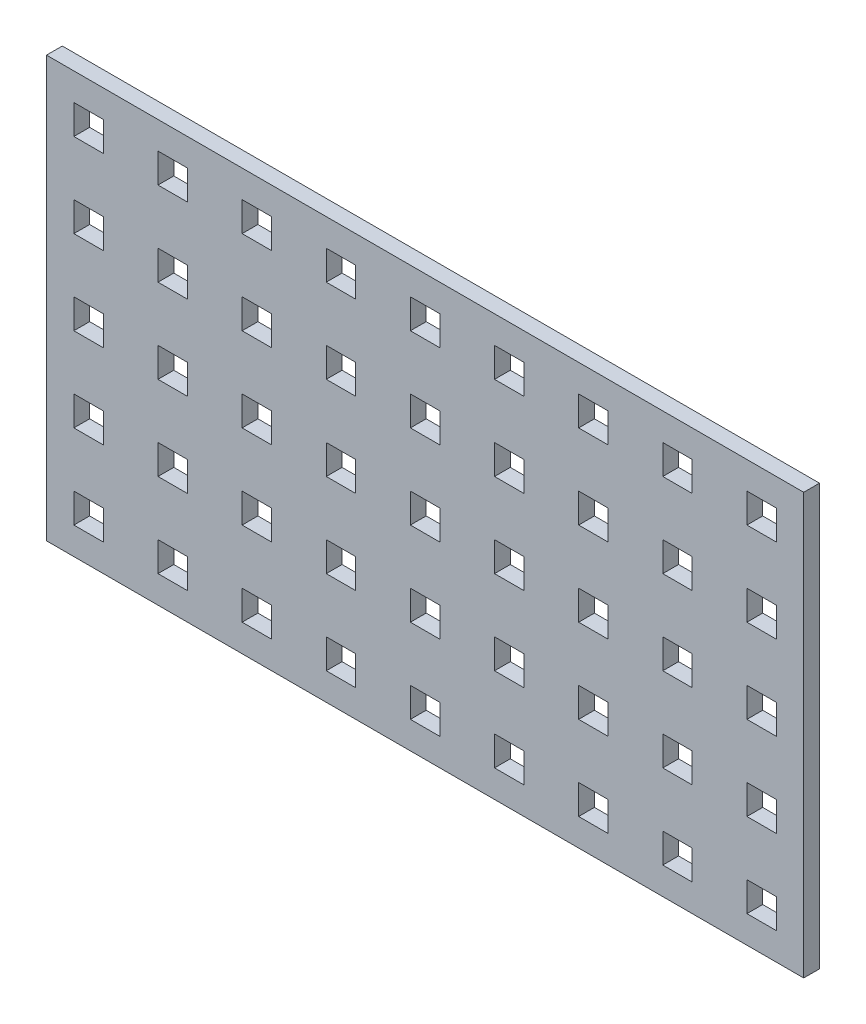
SolidWorks part; units mm, degrees
ref_plane "Plano frontal" through (0, 0, 0) normal (0, 0, 1) x (1, 0, 0)
ref_plane "Plano superior" through (0, 0, 0) normal (0, 1, 0) x (1, 0, 0)
ref_plane "Plano direito" through (0, 0, 0) normal (1, 0, 0) x (0, 0, -1)
sketch "Esboço1" plane through (0, 0, 0) normal (0, 0, 1) x (1, 0, 0)
  line L0 (-36, 0) -> (-32, 0) construction
  line L1 (-36, 20) -> (36, 20)
  line L2 (-36, 20) -> (-36, -20)
  line L3 (-36, -20) -> (36, -20)
  line L4 (36, 20) -> (36, -20)
  line L5 (-36, 20) -> (36, -20) construction
  line L6 (-36, -20) -> (36, 20) construction
  line L7 (-32, 0) -> (-32, 16) construction
  line L8 (-32, 16) -> (32, 16) construction
  line L9 (-33.4, 17.4) -> (-33.4, 14.6)
  line L10 (-25.4, 17.4) -> (-25.4, 14.6)
  line L11 (-22.6, 17.4) -> (-22.6, 14.6)
  line L12 (-25.4, 14.6) -> (-22.6, 14.6)
  line L13 (-25.4, 17.4) -> (-22.6, 17.4)
  line L14 (-25.4, 9.4) -> (-25.4, 6.6)
  line L15 (-22.6, 9.4) -> (-22.6, 6.6)
  line L16 (-30.6, 17.4) -> (-30.6, 14.6)
  line L17 (-33.4, 14.6) -> (-30.6, 14.6)
  line L18 (-33.4, 17.4) -> (-30.6, 14.6) construction
  line L19 (-33.4, 17.4) -> (-30.6, 17.4)
  line L20 (-33.4, 14.6) -> (-30.6, 17.4) construction
  line L21 (30.6, 17.4) -> (30.6, 14.6)
  line L22 (33.4, 17.4) -> (33.4, 14.6)
  line L23 (30.6, 14.6) -> (33.4, 14.6)
  line L24 (30.6, 17.4) -> (33.4, 14.6) construction
  line L25 (30.6, 17.4) -> (33.4, 17.4)
  line L26 (30.6, 14.6) -> (33.4, 17.4) construction
  line L27 (-33.4, 9.4) -> (-33.4, 6.6)
  line L28 (-30.6, 9.4) -> (-30.6, 6.6)
  line L29 (-33.4, 6.6) -> (-30.6, 6.6)
  line L30 (-33.4, 9.4) -> (-30.6, 9.4)
  line L31 (-33.4, 9.4) -> (-30.6, 6.6) construction
  line L32 (-33.4, 6.6) -> (-30.6, 9.4) construction
  line L33 (30.6, 9.4) -> (30.6, 6.6)
  line L34 (33.4, 9.4) -> (33.4, 6.6)
  line L35 (30.6, 6.6) -> (33.4, 6.6)
  line L36 (30.6, 9.4) -> (33.4, 9.4)
  line L37 (30.6, 9.4) -> (33.4, 6.6) construction
  line L38 (30.6, 6.6) -> (33.4, 9.4) construction
  line L39 (-33.4, 1.4) -> (-33.4, -1.4)
  line L40 (-30.6, 1.4) -> (-30.6, -1.4)
  line L41 (-33.4, -1.4) -> (-30.6, -1.4)
  line L42 (-33.4, 1.4) -> (-30.6, 1.4)
  line L43 (-33.4, 1.4) -> (-30.6, -1.4) construction
  line L44 (-33.4, -1.4) -> (-30.6, 1.4) construction
  line L45 (30.6, 1.4) -> (30.6, -1.4)
  line L46 (33.4, 1.4) -> (33.4, -1.4)
  line L47 (30.6, -1.4) -> (33.4, -1.4)
  line L48 (30.6, 1.4) -> (33.4, 1.4)
  line L49 (30.6, 1.4) -> (33.4, -1.4) construction
  line L50 (30.6, -1.4) -> (33.4, 1.4) construction
  line L51 (-33.4, -6.6) -> (-33.4, -9.4)
  line L52 (-30.6, -6.6) -> (-30.6, -9.4)
  line L53 (-33.4, -9.4) -> (-30.6, -9.4)
  line L54 (-33.4, -6.6) -> (-30.6, -6.6)
  line L55 (-33.4, -6.6) -> (-30.6, -9.4) construction
  line L56 (-33.4, -9.4) -> (-30.6, -6.6) construction
  line L57 (30.6, -6.6) -> (30.6, -9.4)
  line L58 (33.4, -6.6) -> (33.4, -9.4)
  line L59 (30.6, -9.4) -> (33.4, -9.4)
  line L60 (30.6, -6.6) -> (33.4, -6.6)
  line L61 (30.6, -6.6) -> (33.4, -9.4) construction
  line L62 (30.6, -9.4) -> (33.4, -6.6) construction
  line L63 (-33.4, -14.6) -> (-33.4, -17.4)
  line L64 (-30.6, -14.6) -> (-30.6, -17.4)
  line L65 (-33.4, -17.4) -> (-30.6, -17.4)
  line L66 (-33.4, -14.6) -> (-30.6, -14.6)
  line L67 (-33.4, -14.6) -> (-30.6, -17.4) construction
  line L68 (-33.4, -17.4) -> (-30.6, -14.6) construction
  line L69 (30.6, -14.6) -> (30.6, -17.4)
  line L70 (33.4, -14.6) -> (33.4, -17.4)
  line L71 (30.6, -17.4) -> (33.4, -17.4)
  line L72 (30.6, -14.6) -> (33.4, -14.6)
  line L73 (30.6, -14.6) -> (33.4, -17.4) construction
  line L74 (30.6, -17.4) -> (33.4, -14.6) construction
  line L75 (-25.4, 6.6) -> (-22.6, 6.6)
  line L76 (-25.4, 9.4) -> (-22.6, 9.4)
  line L77 (-25.4, 1.4) -> (-25.4, -1.4)
  line L78 (-22.6, 1.4) -> (-22.6, -1.4)
  line L79 (-25.4, -1.4) -> (-22.6, -1.4)
  line L80 (-25.4, 1.4) -> (-22.6, 1.4)
  line L81 (-25.4, -6.6) -> (-25.4, -9.4)
  line L82 (-22.6, -6.6) -> (-22.6, -9.4)
  line L83 (-25.4, -9.4) -> (-22.6, -9.4)
  line L84 (-25.4, -6.6) -> (-22.6, -6.6)
  line L85 (-25.4, -14.6) -> (-25.4, -17.4)
  line L86 (-22.6, -14.6) -> (-22.6, -17.4)
  line L87 (-25.4, -17.4) -> (-22.6, -17.4)
  line L88 (-25.4, -14.6) -> (-22.6, -14.6)
  line L89 (-24, 0) -> (-24, 16) construction
  line L90 (-25.4, 17.4) -> (-22.6, 14.6) construction
  line L91 (-25.4, 14.6) -> (-22.6, 17.4) construction
  line L92 (-25.4, 9.4) -> (-22.6, 6.6) construction
  line L93 (-25.4, 6.6) -> (-22.6, 9.4) construction
  line L94 (-25.4, 1.4) -> (-22.6, -1.4) construction
  line L95 (-25.4, -1.4) -> (-22.6, 1.4) construction
  line L96 (-25.4, -6.6) -> (-22.6, -9.4) construction
  line L97 (-25.4, -9.4) -> (-22.6, -6.6) construction
  line L98 (-25.4, -14.6) -> (-22.6, -17.4) construction
  line L99 (-25.4, -17.4) -> (-22.6, -14.6) construction
  line L100 (-17.4, 17.4) -> (-17.4, 14.6)
  line L101 (-14.6, 17.4) -> (-14.6, 14.6)
  line L102 (-17.4, 14.6) -> (-14.6, 14.6)
  line L103 (-17.4, 17.4) -> (-14.6, 17.4)
  line L104 (-17.4, 9.4) -> (-17.4, 6.6)
  line L105 (-14.6, 9.4) -> (-14.6, 6.6)
  line L106 (-17.4, 6.6) -> (-14.6, 6.6)
  line L107 (-17.4, 9.4) -> (-14.6, 9.4)
  line L108 (-17.4, 1.4) -> (-17.4, -1.4)
  line L109 (-14.6, 1.4) -> (-14.6, -1.4)
  line L110 (-17.4, -1.4) -> (-14.6, -1.4)
  line L111 (-17.4, 1.4) -> (-14.6, 1.4)
  line L112 (-17.4, -6.6) -> (-17.4, -9.4)
  line L113 (-14.6, -6.6) -> (-14.6, -9.4)
  line L114 (-17.4, -9.4) -> (-14.6, -9.4)
  line L115 (-17.4, -6.6) -> (-14.6, -6.6)
  line L116 (-17.4, -14.6) -> (-17.4, -17.4)
  line L117 (-14.6, -14.6) -> (-14.6, -17.4)
  line L118 (-17.4, -17.4) -> (-14.6, -17.4)
  line L119 (-17.4, -14.6) -> (-14.6, -14.6)
  line L120 (-16, 0) -> (-16, 16) construction
  line L121 (-17.4, 17.4) -> (-14.6, 14.6) construction
  line L122 (-17.4, 14.6) -> (-14.6, 17.4) construction
  line L123 (-17.4, 9.4) -> (-14.6, 6.6) construction
  line L124 (-17.4, 6.6) -> (-14.6, 9.4) construction
  line L125 (-17.4, 1.4) -> (-14.6, -1.4) construction
  line L126 (-17.4, -1.4) -> (-14.6, 1.4) construction
  line L127 (-17.4, -6.6) -> (-14.6, -9.4) construction
  line L128 (-17.4, -9.4) -> (-14.6, -6.6) construction
  line L129 (-17.4, -14.6) -> (-14.6, -17.4) construction
  line L130 (-17.4, -17.4) -> (-14.6, -14.6) construction
  line L131 (-9.4, 17.4) -> (-9.4, 14.6)
  line L132 (-6.6, 17.4) -> (-6.6, 14.6)
  line L133 (-9.4, 14.6) -> (-6.6, 14.6)
  line L134 (-9.4, 17.4) -> (-6.6, 17.4)
  line L135 (-9.4, 9.4) -> (-9.4, 6.6)
  line L136 (-6.6, 9.4) -> (-6.6, 6.6)
  line L137 (-9.4, 6.6) -> (-6.6, 6.6)
  line L138 (-9.4, 9.4) -> (-6.6, 9.4)
  line L139 (-9.4, 1.4) -> (-9.4, -1.4)
  line L140 (-6.6, 1.4) -> (-6.6, -1.4)
  line L141 (-9.4, -1.4) -> (-6.6, -1.4)
  line L142 (-9.4, 1.4) -> (-6.6, 1.4)
  line L143 (-9.4, -6.6) -> (-9.4, -9.4)
  line L144 (-6.6, -6.6) -> (-6.6, -9.4)
  line L145 (-9.4, -9.4) -> (-6.6, -9.4)
  line L146 (-9.4, -6.6) -> (-6.6, -6.6)
  line L147 (-9.4, -14.6) -> (-9.4, -17.4)
  line L148 (-6.6, -14.6) -> (-6.6, -17.4)
  line L149 (-9.4, -17.4) -> (-6.6, -17.4)
  line L150 (-9.4, -14.6) -> (-6.6, -14.6)
  line L151 (-8, 0) -> (-8, 16) construction
  line L152 (-9.4, 17.4) -> (-6.6, 14.6) construction
  line L153 (-9.4, 14.6) -> (-6.6, 17.4) construction
  line L154 (-9.4, 9.4) -> (-6.6, 6.6) construction
  line L155 (-9.4, 6.6) -> (-6.6, 9.4) construction
  line L156 (-9.4, 1.4) -> (-6.6, -1.4) construction
  line L157 (-9.4, -1.4) -> (-6.6, 1.4) construction
  line L158 (-9.4, -6.6) -> (-6.6, -9.4) construction
  line L159 (-9.4, -9.4) -> (-6.6, -6.6) construction
  line L160 (-9.4, -14.6) -> (-6.6, -17.4) construction
  line L161 (-9.4, -17.4) -> (-6.6, -14.6) construction
  line L162 (-1.4, 17.4) -> (-1.4, 14.6)
  line L163 (1.4, 17.4) -> (1.4, 14.6)
  line L164 (-1.4, 14.6) -> (1.4, 14.6)
  line L165 (-1.4, 17.4) -> (1.4, 17.4)
  line L166 (-1.4, 9.4) -> (-1.4, 6.6)
  line L167 (1.4, 9.4) -> (1.4, 6.6)
  line L168 (-1.4, 6.6) -> (1.4, 6.6)
  line L169 (-1.4, 9.4) -> (1.4, 9.4)
  line L170 (-1.4, 1.4) -> (-1.4, -1.4)
  line L171 (1.4, 1.4) -> (1.4, -1.4)
  line L172 (-1.4, -1.4) -> (1.4, -1.4)
  line L173 (-1.4, 1.4) -> (1.4, 1.4)
  line L174 (-1.4, -6.6) -> (-1.4, -9.4)
  line L175 (1.4, -6.6) -> (1.4, -9.4)
  line L176 (-1.4, -9.4) -> (1.4, -9.4)
  line L177 (-1.4, -6.6) -> (1.4, -6.6)
  line L178 (-1.4, -14.6) -> (-1.4, -17.4)
  line L179 (1.4, -14.6) -> (1.4, -17.4)
  line L180 (-1.4, -17.4) -> (1.4, -17.4)
  line L181 (-1.4, -14.6) -> (1.4, -14.6)
  line L182 (0, 0) -> (0, 16) construction
  line L183 (-1.4, 17.4) -> (1.4, 14.6) construction
  line L184 (-1.4, 14.6) -> (1.4, 17.4) construction
  line L185 (-1.4, 9.4) -> (1.4, 6.6) construction
  line L186 (-1.4, 6.6) -> (1.4, 9.4) construction
  line L187 (-1.4, 1.4) -> (1.4, -1.4) construction
  line L188 (-1.4, -1.4) -> (1.4, 1.4) construction
  line L189 (-1.4, -6.6) -> (1.4, -9.4) construction
  line L190 (-1.4, -9.4) -> (1.4, -6.6) construction
  line L191 (-1.4, -14.6) -> (1.4, -17.4) construction
  line L192 (-1.4, -17.4) -> (1.4, -14.6) construction
  line L193 (6.6, 17.4) -> (6.6, 14.6)
  line L194 (9.4, 17.4) -> (9.4, 14.6)
  line L195 (6.6, 14.6) -> (9.4, 14.6)
  line L196 (6.6, 17.4) -> (9.4, 17.4)
  line L197 (6.6, 9.4) -> (6.6, 6.6)
  line L198 (9.4, 9.4) -> (9.4, 6.6)
  line L199 (6.6, 6.6) -> (9.4, 6.6)
  line L200 (6.6, 9.4) -> (9.4, 9.4)
  line L201 (6.6, 1.4) -> (6.6, -1.4)
  line L202 (9.4, 1.4) -> (9.4, -1.4)
  line L203 (6.6, -1.4) -> (9.4, -1.4)
  line L204 (6.6, 1.4) -> (9.4, 1.4)
  line L205 (6.6, -6.6) -> (6.6, -9.4)
  line L206 (9.4, -6.6) -> (9.4, -9.4)
  line L207 (6.6, -9.4) -> (9.4, -9.4)
  line L208 (6.6, -6.6) -> (9.4, -6.6)
  line L209 (6.6, -14.6) -> (6.6, -17.4)
  line L210 (9.4, -14.6) -> (9.4, -17.4)
  line L211 (6.6, -17.4) -> (9.4, -17.4)
  line L212 (6.6, -14.6) -> (9.4, -14.6)
  line L213 (8, 0) -> (8, 16) construction
  line L214 (6.6, 17.4) -> (9.4, 14.6) construction
  line L215 (6.6, 14.6) -> (9.4, 17.4) construction
  line L216 (6.6, 9.4) -> (9.4, 6.6) construction
  line L217 (6.6, 6.6) -> (9.4, 9.4) construction
  line L218 (6.6, 1.4) -> (9.4, -1.4) construction
  line L219 (6.6, -1.4) -> (9.4, 1.4) construction
  line L220 (6.6, -6.6) -> (9.4, -9.4) construction
  line L221 (6.6, -9.4) -> (9.4, -6.6) construction
  line L222 (6.6, -14.6) -> (9.4, -17.4) construction
  line L223 (6.6, -17.4) -> (9.4, -14.6) construction
  line L224 (14.6, 17.4) -> (14.6, 14.6)
  line L225 (17.4, 17.4) -> (17.4, 14.6)
  line L226 (14.6, 14.6) -> (17.4, 14.6)
  line L227 (14.6, 17.4) -> (17.4, 17.4)
  line L228 (14.6, 9.4) -> (14.6, 6.6)
  line L229 (17.4, 9.4) -> (17.4, 6.6)
  line L230 (14.6, 6.6) -> (17.4, 6.6)
  line L231 (14.6, 9.4) -> (17.4, 9.4)
  line L232 (14.6, 1.4) -> (14.6, -1.4)
  line L233 (17.4, 1.4) -> (17.4, -1.4)
  line L234 (14.6, -1.4) -> (17.4, -1.4)
  line L235 (14.6, 1.4) -> (17.4, 1.4)
  line L236 (14.6, -6.6) -> (14.6, -9.4)
  line L237 (17.4, -6.6) -> (17.4, -9.4)
  line L238 (14.6, -9.4) -> (17.4, -9.4)
  line L239 (14.6, -6.6) -> (17.4, -6.6)
  line L240 (14.6, -14.6) -> (14.6, -17.4)
  line L241 (17.4, -14.6) -> (17.4, -17.4)
  line L242 (14.6, -17.4) -> (17.4, -17.4)
  line L243 (14.6, -14.6) -> (17.4, -14.6)
  line L244 (16, 0) -> (16, 16) construction
  line L245 (14.6, 17.4) -> (17.4, 14.6) construction
  line L246 (14.6, 14.6) -> (17.4, 17.4) construction
  line L247 (14.6, 9.4) -> (17.4, 6.6) construction
  line L248 (14.6, 6.6) -> (17.4, 9.4) construction
  line L249 (14.6, 1.4) -> (17.4, -1.4) construction
  line L250 (14.6, -1.4) -> (17.4, 1.4) construction
  line L251 (14.6, -6.6) -> (17.4, -9.4) construction
  line L252 (14.6, -9.4) -> (17.4, -6.6) construction
  line L253 (14.6, -14.6) -> (17.4, -17.4) construction
  line L254 (14.6, -17.4) -> (17.4, -14.6) construction
  line L255 (22.6, 17.4) -> (22.6, 14.6)
  line L256 (25.4, 17.4) -> (25.4, 14.6)
  line L257 (22.6, 14.6) -> (25.4, 14.6)
  line L258 (22.6, 17.4) -> (25.4, 17.4)
  line L259 (22.6, 9.4) -> (22.6, 6.6)
  line L260 (25.4, 9.4) -> (25.4, 6.6)
  line L261 (22.6, 6.6) -> (25.4, 6.6)
  line L262 (22.6, 9.4) -> (25.4, 9.4)
  line L263 (22.6, 1.4) -> (22.6, -1.4)
  line L264 (25.4, 1.4) -> (25.4, -1.4)
  line L265 (22.6, -1.4) -> (25.4, -1.4)
  line L266 (22.6, 1.4) -> (25.4, 1.4)
  line L267 (22.6, -6.6) -> (22.6, -9.4)
  line L268 (25.4, -6.6) -> (25.4, -9.4)
  line L269 (22.6, -9.4) -> (25.4, -9.4)
  line L270 (22.6, -6.6) -> (25.4, -6.6)
  line L271 (22.6, -14.6) -> (22.6, -17.4)
  line L272 (25.4, -14.6) -> (25.4, -17.4)
  line L273 (22.6, -17.4) -> (25.4, -17.4)
  line L274 (22.6, -14.6) -> (25.4, -14.6)
  line L275 (24, 0) -> (24, 16) construction
  line L276 (22.6, 17.4) -> (25.4, 14.6) construction
  line L277 (22.6, 14.6) -> (25.4, 17.4) construction
  line L278 (22.6, 9.4) -> (25.4, 6.6) construction
  line L279 (22.6, 6.6) -> (25.4, 9.4) construction
  line L280 (22.6, 1.4) -> (25.4, -1.4) construction
  line L281 (22.6, -1.4) -> (25.4, 1.4) construction
  line L282 (22.6, -6.6) -> (25.4, -9.4) construction
  line L283 (22.6, -9.4) -> (25.4, -6.6) construction
  line L284 (22.6, -14.6) -> (25.4, -17.4) construction
  line L285 (22.6, -17.4) -> (25.4, -14.6) construction
  point P0 (0, 0)
  point P13 (-24, 16)
  point P15 (-32, 16)
  point P20 (32, 16)
  point P27 (-32, 8)
  point P32 (32, 8)
  point P37 (-32, 0)
  point P42 (32, 0)
  point P47 (-32, -8)
  point P52 (32, -8)
  point P57 (-32, -16)
  point P62 (32, -16)
  point P68 (-24, 8)
  point P73 (-24, 0)
  point P78 (-24, -8)
  point P83 (-24, -16)
  point P90 (-16, 16)
  point P95 (-16, 8)
  point P100 (-16, 0)
  point P105 (-16, -8)
  point P110 (-16, -16)
  point P117 (-8, 16)
  point P122 (-8, 8)
  point P127 (-8, 0)
  point P132 (-8, -8)
  point P137 (-8, -16)
  point P144 (0, 16)
  point P149 (0, 8)
  point P154 (0, 0)
  point P159 (0, -8)
  point P164 (0, -16)
  point P171 (8, 16)
  point P176 (8, 8)
  point P181 (8, 0)
  point P186 (8, -8)
  point P191 (8, -16)
  point P198 (16, 16)
  point P203 (16, 8)
  point P208 (16, 0)
  point P213 (16, -8)
  point P218 (16, -16)
  point P225 (24, 16)
  point P230 (24, 8)
  point P235 (24, 0)
  point P240 (24, -8)
  point P245 (24, -16)
  dimension "D1" = 8
  dimension "D2" = 2.8
  dimension "D3" = 2.8
  dimension "D4" = 5
extrude "Ressalto-extrusão1" add sketch "Esboço1" along normal blind 1.5
